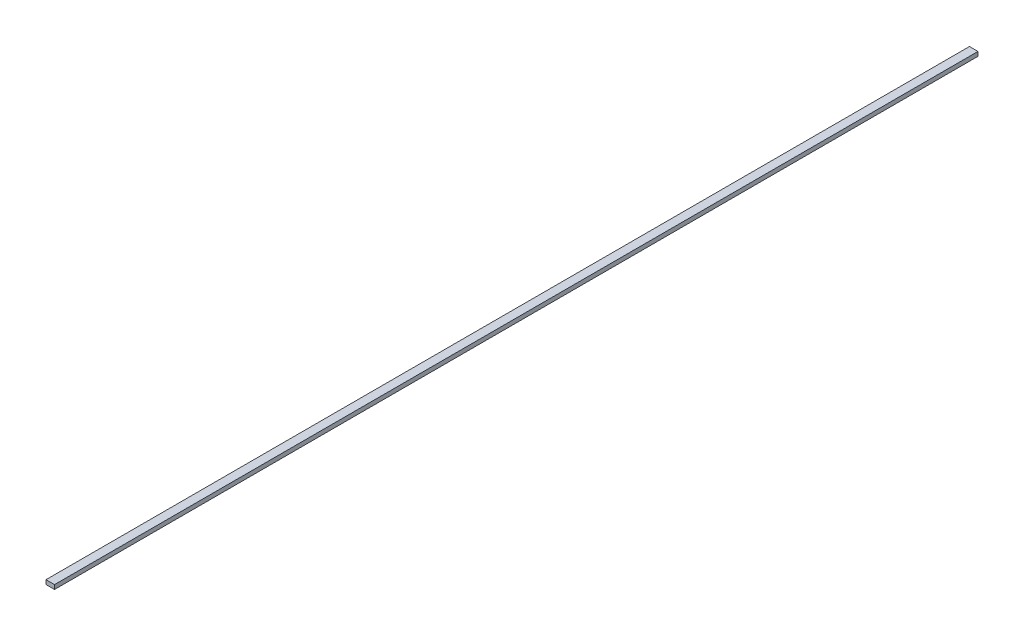
SolidWorks part; units mm, degrees
ref_plane "Front Plane" through (0, 0, 0) normal (0, 0, 1) x (1, 0, 0)
ref_plane "Top Plane" through (0, 0, 0) normal (0, 1, 0) x (1, 0, 0)
ref_plane "Right Plane" through (0, 0, 0) normal (1, 0, 0) x (0, 0, -1)
other "Configuration Table"
sketch "Sketch1" plane through (0, 0, 0) normal (0, 0, 1) x (1, 0, 0)
  line L1 (0, 0) -> (6, 0)
  line L2 (0, 0) -> (0, 3)
  line L3 (0, 3) -> (6, 3)
  line L4 (6, 0) -> (6, 3)
extrude "KAYIS_GT3_6x3x650_1" add sketch "Sketch1" against normal blind 650 from offset 40 separate body
